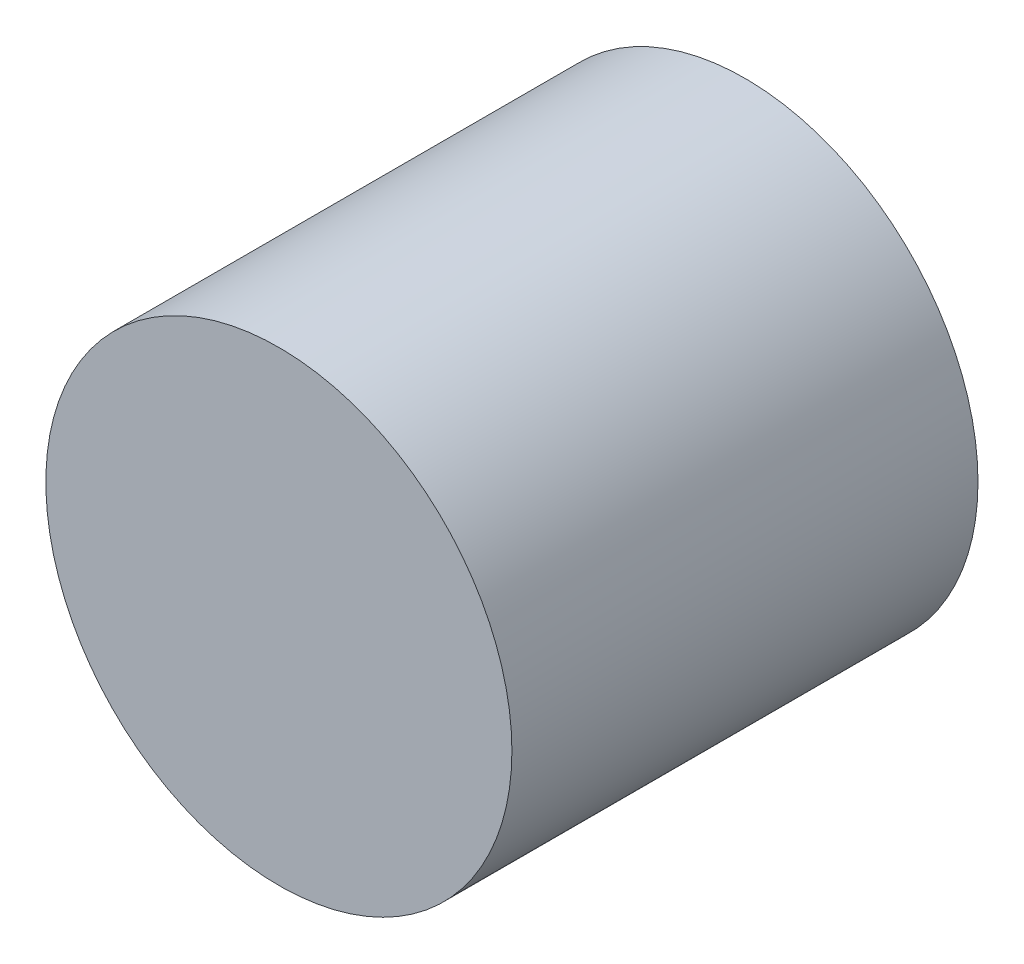
SolidWorks part; units mm, degrees
ref_plane "前视基准面" through (0, 0, 0) normal (0, 0, 1) x (1, 0, 0)
ref_plane "上视基准面" through (0, 0, 0) normal (0, 1, 0) x (1, 0, 0)
ref_plane "右视基准面" through (0, 0, 0) normal (1, 0, 0) x (0, 0, -1)
sketch "草图1" plane through (0, 0, 0) normal (0, 0, 1) x (1, 0, 0)
  circle A0 centre (0, 0) radius 10
  dimension "D1" = 20
extrude "凸台-拉伸1" add sketch "草图1" along normal blind 20
hole_wizard "Ø2.5mm 暗销孔1" positions "草图2" profile "草图4" hole size "Ø2.5" standard "ISO"
sketch "草图2" plane through (0, 0, 0) normal (0, 0, -1) x (-1, 0, 0)
  point P0 (0, 0)
sketch "草图4" plane through (0, 0, 0) normal (1, 0, 0) x (0, 1, 0)
  line L0 (0, 0) -> (0, 10.7511)
  line L1 (0, 10.7511) -> (1.25, 10)
  line L2 (1.25, 10) -> (1.25, 0.025)
  line L3 (1.25, 0.025) -> (1.275, 0)
  line L5 (1.275, 0) -> (0, 0)
  line L6 (-1.25, 0.025) -> (-1.275, 0) construction
  line L10 (0, 10.7511) -> (-1.25, 10) construction
  line L11 (0, -6.35) -> (0, 107.95) construction
  dimension "孔直径" = 2.5
  dimension "孔深度" = 10
  dimension "近端锥形沉头孔直径" = 2.55
  dimension "近端锥形沉头孔角度" = 90
  dimension "导头角度" = 118
